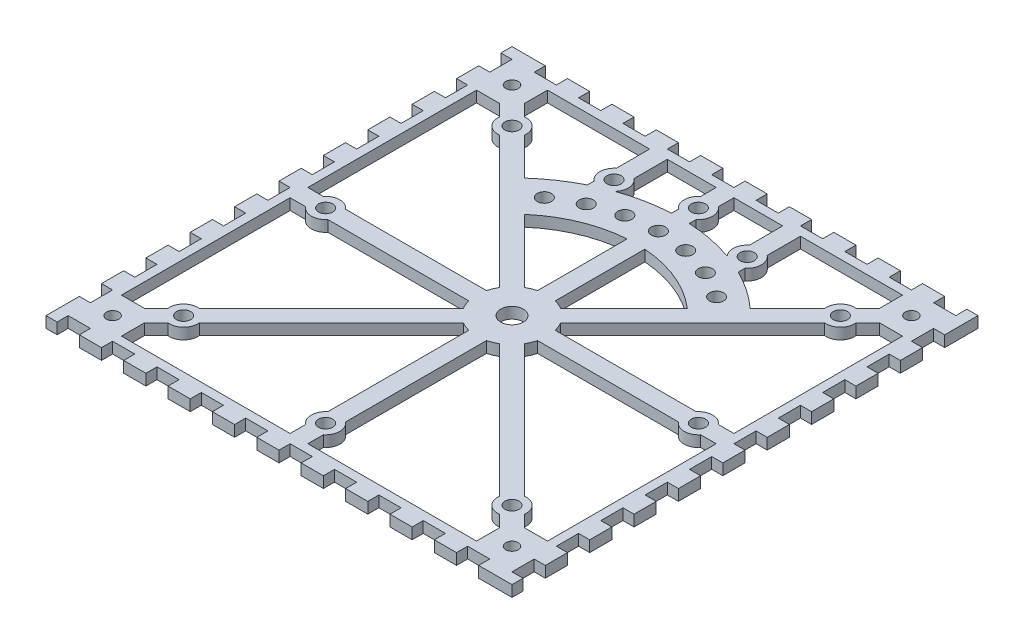
SolidWorks part; units mm, degrees
ref_plane "Front Plane" through (0, 0, 0) normal (0, 0, 1) x (1, 0, 0)
ref_plane "Top Plane" through (0, 0, 0) normal (0, 1, 0) x (1, 0, 0)
ref_plane "Right Plane" through (0, 0, 0) normal (1, 0, 0) x (0, 0, -1)
sketch "Sketch1" plane through (0, 0, 0) normal (0, 1, 0) x (1, 0, 0)
  line L480 (-40, 48) -> (-17, 48)
  line L481 (-48, 40) -> (-48, 2)
  line L483 (-40, -48) -> (-2, -48)
  line L484 (48, 40) -> (48, 2)
  line L486 (48, 2) -> (44.498, 2)
  line L487 (48, -2) -> (48, -40)
  line L488 (40, -42.8284) -> (37.3521, -40.1806)
  line L489 (48, -2) -> (44.498, -2)
  line L490 (-2, -48) -> (-2, -44.498)
  line L491 (2, -48) -> (40, -48)
  line L494 (-40, -42.8284) -> (-37.3521, -40.1806)
  line L496 (-48, -2) -> (-44.498, -2)
  line L497 (-48, 2) -> (-44.498, 2)
  line L498 (-40, 42.8284) -> (-37.3521, 40.1806)
  line L499 (2, 48) -> (2, 44.498)
  line L500 (-33.8194, 36.6479) -> (-25.4186, 28.247)
  line L501 (-36.6479, 33.8194) -> (-6.8914, 4.063)
  line L502 (-2, 39.502) -> (-2, 37.9473)
  line L503 (2, 39.502) -> (2, 37.9473)
  line L504 (33.8194, 36.6479) -> (25.4186, 28.247)
  line L505 (36.6479, 33.8194) -> (6.8914, 4.063)
  line L506 (39.502, 2) -> (7.746, 2)
  line L507 (39.502, -2) -> (7.746, -2)
  line L508 (33.8194, -36.6479) -> (4.063, -6.8914)
  line L509 (36.6479, -33.8194) -> (6.8914, -4.063)
  line L510 (-2, -39.502) -> (-2, -7.746)
  line L511 (2, -39.502) -> (2, -7.746)
  line L513 (-33.8194, -36.6479) -> (-4.063, -6.8914)
  line L514 (-39.502, 2) -> (-7.746, 2)
  line L515 (-39.502, -2) -> (-7.746, -2)
  line L516 (-48, -2) -> (-48, -40)
  line L517 (-42.8284, 40) -> (-40.1806, 37.3521)
  line L518 (-50, 52.5) -> (-45, 52.5)
  line L519 (-45, 52.5) -> (-45, 50)
  line L520 (2, 48) -> (13, 48)
  line L521 (-2, 48) -> (-2, 44.498)
  line L522 (40, 42.8284) -> (37.3521, 40.1806)
  line L523 (42.8284, 40) -> (40.1806, 37.3521)
  line L524 (-45, 50) -> (-40, 50)
  line L525 (-40, 50) -> (-40, 52.5)
  line L526 (-40, 52.5) -> (-35, 52.5)
  line L527 (42.8284, -40) -> (40.1806, -37.3521)
  line L528 (-35, 52.5) -> (-35, 50)
  line L529 (-35, 50) -> (-30, 50)
  line L530 (2, -48) -> (2, -44.498)
  line L531 (-42.8284, -40) -> (-40.1806, -37.3521)
  line L532 (-30, 50) -> (-30, 52.5)
  line L546 (-30, 52.5) -> (-25, 52.5)
  line L547 (-25, 52.5) -> (-25, 50)
  line L548 (-25, 50) -> (-20, 50)
  line L549 (-20, 50) -> (-20, 52.5)
  line L550 (-20, 52.5) -> (-15, 52.5)
  line L551 (-15, 52.5) -> (-15, 50)
  line L552 (-15, 50) -> (-10, 50)
  line L553 (-10, 50) -> (-10, 52.5)
  line L554 (-10, 52.5) -> (-5, 52.5)
  line L555 (-5, 52.5) -> (-5, 50)
  line L556 (-5, 50) -> (0, 50)
  line L557 (0, 50) -> (0, 52.5)
  line L558 (0, 52.5) -> (5, 52.5)
  line L559 (5, 52.5) -> (5, 50)
  line L560 (5, 50) -> (10, 50)
  line L561 (10, 50) -> (10, 52.5)
  line L562 (10, 52.5) -> (15, 52.5)
  line L563 (15, 52.5) -> (15, 50)
  line L564 (15, 50) -> (20, 50)
  line L565 (20, 50) -> (20, 52.5)
  line L566 (20, 52.5) -> (25, 52.5)
  line L567 (25, 52.5) -> (25, 50)
  line L568 (25, 50) -> (30, 50)
  line L569 (30, 50) -> (30, 52.5)
  line L570 (30, 52.5) -> (35, 52.5)
  line L571 (35, 52.5) -> (35, 50)
  line L572 (35, 50) -> (40, 50)
  line L573 (40, 50) -> (40, 52.5)
  line L574 (40, 52.5) -> (45, 52.5)
  line L575 (45, 52.5) -> (45, 50)
  line L576 (45, 50) -> (50, 50)
  line L578 (52.5, 50) -> (52.5, 45)
  line L579 (52.5, 45) -> (50, 45)
  line L580 (50, 45) -> (50, 40)
  line L582 (50, 40) -> (52.5, 40)
  line L583 (52.5, 40) -> (52.5, 35)
  line L584 (52.5, 35) -> (50, 35)
  line L585 (50, 35) -> (50, 30)
  line L586 (50, 30) -> (52.5, 30)
  line L587 (52.5, 30) -> (52.5, 25)
  line L588 (52.5, 25) -> (50, 25)
  line L589 (50, 25) -> (50, 20)
  line L590 (50, 20) -> (52.5, 20)
  line L591 (52.5, 20) -> (52.5, 15)
  line L592 (52.5, 15) -> (50, 15)
  line L593 (50, 15) -> (50, 10)
  line L594 (50, 10) -> (52.5, 10)
  line L595 (52.5, 10) -> (52.5, 5)
  line L596 (52.5, 5) -> (50, 5)
  line L597 (50, 5) -> (50, 0)
  line L598 (50, 0) -> (52.5, 0)
  line L599 (52.5, 0) -> (52.5, -5)
  line L600 (52.5, -5) -> (50, -5)
  line L601 (50, -5) -> (50, -10)
  line L602 (50, -10) -> (52.5, -10)
  line L603 (52.5, -10) -> (52.5, -15)
  line L604 (52.5, -15) -> (50, -15)
  line L605 (50, -15) -> (50, -20)
  line L606 (50, -20) -> (52.5, -20)
  line L607 (52.5, -20) -> (52.5, -25)
  line L608 (52.5, -25) -> (50, -25)
  line L609 (50, -25) -> (50, -30)
  line L610 (50, -30) -> (52.5, -30)
  line L611 (52.5, -30) -> (52.5, -35)
  line L612 (52.5, -35) -> (50, -35)
  line L613 (50, -35) -> (50, -40)
  line L614 (50, -40) -> (52.5, -40)
  line L615 (52.5, -40) -> (52.5, -45)
  line L616 (52.5, -45) -> (50, -45)
  line L617 (50, -45) -> (50, -50)
  line L619 (50, -52.5) -> (45, -52.5)
  line L620 (45, -52.5) -> (45, -50)
  line L621 (45, -50) -> (40, -50)
  line L623 (40, -50) -> (40, -52.5)
  line L624 (40, -52.5) -> (35, -52.5)
  line L625 (35, -52.5) -> (35, -50)
  line L626 (35, -50) -> (30, -50)
  line L627 (30, -50) -> (30, -52.5)
  line L628 (30, -52.5) -> (25, -52.5)
  line L629 (25, -52.5) -> (25, -50)
  line L630 (25, -50) -> (20, -50)
  line L631 (20, -50) -> (20, -52.5)
  line L632 (20, -52.5) -> (15, -52.5)
  line L633 (15, -52.5) -> (15, -50)
  line L634 (15, -50) -> (10, -50)
  line L635 (10, -50) -> (10, -52.5)
  line L636 (10, -52.5) -> (5, -52.5)
  line L637 (5, -52.5) -> (5, -50)
  line L638 (5, -50) -> (0, -50)
  line L639 (0, -50) -> (0, -52.5)
  line L640 (0, -52.5) -> (-5, -52.5)
  line L641 (-5, -52.5) -> (-5, -50)
  line L642 (-5, -50) -> (-10, -50)
  line L643 (-10, -50) -> (-10, -52.5)
  line L644 (-10, -52.5) -> (-15, -52.5)
  line L645 (-15, -52.5) -> (-15, -50)
  line L646 (-15, -50) -> (-20, -50)
  line L647 (-20, -50) -> (-20, -52.5)
  line L648 (-20, -52.5) -> (-25, -52.5)
  line L649 (-25, -52.5) -> (-25, -50)
  line L650 (-25, -50) -> (-30, -50)
  line L651 (-30, -50) -> (-30, -52.5)
  line L652 (-30, -52.5) -> (-35, -52.5)
  line L653 (-35, -52.5) -> (-35, -50)
  line L654 (-35, -50) -> (-40, -50)
  line L655 (-40, -50) -> (-40, -52.5)
  line L656 (-40, -52.5) -> (-45, -52.5)
  line L657 (-45, -52.5) -> (-45, -50)
  line L658 (-45, -50) -> (-50, -50)
  line L660 (-52.5, -50) -> (-52.5, -45)
  line L661 (-52.5, -45) -> (-50, -45)
  line L662 (-50, -45) -> (-50, -40)
  line L664 (-50, -40) -> (-52.5, -40)
  line L665 (-52.5, -40) -> (-52.5, -35)
  line L666 (-52.5, -35) -> (-50, -35)
  line L667 (-50, -35) -> (-50, -30)
  line L668 (-50, -30) -> (-52.5, -30)
  line L669 (-52.5, -30) -> (-52.5, -25)
  line L670 (-52.5, -25) -> (-50, -25)
  line L671 (-50, -25) -> (-50, -20)
  line L672 (-50, -20) -> (-52.5, -20)
  line L673 (-52.5, -20) -> (-52.5, -15)
  line L674 (-52.5, -15) -> (-50, -15)
  line L675 (-50, -15) -> (-50, -10)
  line L676 (-50, -10) -> (-52.5, -10)
  line L677 (-52.5, -10) -> (-52.5, -5)
  line L678 (-52.5, -5) -> (-50, -5)
  line L679 (-50, -5) -> (-50, 0)
  line L680 (-50, 0) -> (-52.5, 0)
  line L681 (-52.5, 0) -> (-52.5, 5)
  line L682 (-52.5, 5) -> (-50, 5)
  line L683 (-50, 5) -> (-50, 10)
  line L684 (-50, 10) -> (-52.5, 10)
  line L685 (-52.5, 10) -> (-52.5, 15)
  line L686 (-52.5, 15) -> (-50, 15)
  line L687 (-50, 15) -> (-50, 20)
  line L688 (-50, 20) -> (-52.5, 20)
  line L689 (-52.5, 20) -> (-52.5, 25)
  line L690 (-52.5, 25) -> (-50, 25)
  line L691 (-50, 25) -> (-50, 30)
  line L692 (-50, 30) -> (-52.5, 30)
  line L693 (-52.5, 30) -> (-52.5, 35)
  line L694 (-52.5, 35) -> (-50, 35)
  line L695 (-50, 35) -> (-50, 40)
  line L696 (-50, 40) -> (-52.5, 40)
  line L697 (-52.5, 40) -> (-52.5, 45)
  line L698 (-52.5, 45) -> (-50, 45)
  line L699 (-50, 45) -> (-50, 50)
  line L703 (-48, 40) -> (-42.8284, 40)
  line L704 (-40, 48) -> (-40, 42.8284)
  line L708 (48, 40) -> (42.8284, 40)
  line L709 (40, 48) -> (40, 42.8284)
  line L713 (48, -40) -> (42.8284, -40)
  line L714 (40, -48) -> (40, -42.8284)
  line L718 (-48, -40) -> (-42.8284, -40)
  line L719 (-40, -48) -> (-40, -42.8284)
  line L720 (-6.8914, -4.063) -> (-36.6479, -33.8194)
  line L725 (-18.3342, 21.1626) -> (-4.063, 6.8914)
  line L726 (18.3342, 21.1626) -> (4.063, 6.8914)
  line L727 (-17, 48) -> (-17, 40.498)
  line L729 (-13, 48) -> (-13, 40.498)
  line L731 (13, 48) -> (13, 40.498)
  line L733 (17, 48) -> (17, 40.498)
  line L735 (-13, 48) -> (-2, 48)
  line L736 (17, 48) -> (40, 48)
  line L737 (-2, 27.9285) -> (-2, 7.746)
  line L738 (2, 27.9285) -> (2, 7.746)
  line L739 (-17, 35.502) -> (-17, 33.9853)
  line L740 (17, 35.502) -> (17, 33.9853)
  line L743 (-50, 50) -> (-52.5, 50)
  line L745 (-50, 52.5) -> (-52.5, 52.5)
  line L746 (-52.5, 50) -> (-52.5, 52.5)
  line L749 (52.5, 50) -> (52.5, 52.5)
  line L750 (52.5, 52.5) -> (50, 52.5)
  line L751 (50, 50) -> (50, 52.5)
  line L753 (50, -50) -> (52.5, -50)
  line L755 (50, -52.5) -> (52.5, -52.5)
  line L756 (52.5, -50) -> (52.5, -52.5)
  line L759 (-52.5, -50) -> (-52.5, -52.5)
  line L760 (-52.5, -52.5) -> (-50, -52.5)
  line L761 (-50, -50) -> (-50, -52.5)
  circle A10 centre (0, 0) radius 2.55
  arc A14 (-6.8914, 4.063) -> (-7.746, 2) centre (0, 0) ccw
  arc A15 (4.063, 6.8914) -> (2, 7.746) centre (0, 0) ccw
  arc A16 (6.8914, -4.063) -> (7.746, -2) centre (0, 0) ccw
  arc A17 (-4.063, -6.8914) -> (-2, -7.746) centre (0, 0) ccw
  circle A51 centre (37, -37) radius 1.6
  circle A52 centre (-37, -37) radius 1.6
  circle A53 centre (-37, 37) radius 1.6
  circle A56 centre (37, 37) radius 1.6
  arc A73 (-7.746, -2) -> (-6.8914, -4.063) centre (0, 0) ccw
  arc A74 (-2, 7.746) -> (-4.063, 6.8914) centre (0, 0) ccw
  arc A75 (2, -7.746) -> (4.063, -6.8914) centre (0, 0) ccw
  arc A76 (7.746, 2) -> (6.8914, 4.063) centre (0, 0) ccw
  arc A85 (-40.1806, 37.3521) -> (-36.6479, 33.8194) centre (-37, 37) ccw
  arc A86 (36.6479, 33.8194) -> (40.1806, 37.3521) centre (37, 37) ccw
  arc A87 (33.8194, -36.6479) -> (37.3521, -40.1806) centre (37, -37) ccw
  circle A88 centre (0, 42) radius 1.6
  circle A89 centre (42, 0) radius 1.6
  circle A90 centre (-42, 0) radius 1.6
  circle A91 centre (0, -42) radius 1.6
  arc A92 (-44.498, -2) -> (-39.502, -2) centre (-42, 0) ccw
  arc A93 (-2, 44.498) -> (-2, 39.502) centre (0, 42) ccw
  arc A94 (39.502, -2) -> (44.498, -2) centre (42, 0) ccw
  arc A95 (-2, -39.502) -> (-2, -44.498) centre (0, -42) ccw
  arc A96 (-39.502, 2) -> (-44.498, 2) centre (-42, 0) ccw
  arc A97 (2, 39.502) -> (2, 44.498) centre (0, 42) ccw
  arc A98 (44.498, 2) -> (39.502, 2) centre (42, 0) ccw
  arc A99 (2, -44.498) -> (2, -39.502) centre (0, -42) ccw
  arc A100 (-37.3521, -40.1806) -> (-33.8194, -36.6479) centre (-37, -37) ccw
  arc A101 (-33.8194, 36.6479) -> (-37.3521, 40.1806) centre (-37, 37) ccw
  arc A102 (37.3521, 40.1806) -> (33.8194, 36.6479) centre (37, 37) ccw
  arc A103 (40.1806, -37.3521) -> (36.6479, -33.8194) centre (37, -37) ccw
  arc A104 (-36.6479, -33.8194) -> (-40.1806, -37.3521) centre (-37, -37) ccw
  circle A131 centre (-45, 45) radius 1.4
  circle A132 centre (45, 45) radius 1.4
  circle A133 centre (-45, -45) radius 1.4
  circle A134 centre (45, -45) radius 1.4
  circle A135 centre (0, 0) radius 33 construction
  arc A137 (18.3342, 21.1626) -> (2, 27.9285) centre (0, 0) ccw construction
  circle A138 centre (-15, 38) radius 1.6
  circle A139 centre (15, 38) radius 1.6
  arc A140 (18.3342, 21.1626) -> (2, 27.9285) centre (0, 0) ccw
  arc A142 (12.6437, 35.8349) -> (2, 37.9473) centre (0, 0) ccw construction
  arc A143 (12.6437, 35.8349) -> (2, 37.9473) centre (0, 0) ccw
  arc A144 (25.4186, 28.247) -> (17, 33.9853) centre (0, 0) ccw construction
  arc A145 (25.4186, 28.247) -> (17, 33.9853) centre (0, 0) ccw
  arc A146 (-17, 33.9853) -> (-25.4186, 28.247) centre (0, 0) ccw construction
  arc A147 (-17, 33.9853) -> (-25.4186, 28.247) centre (0, 0) ccw
  arc A148 (-2, 37.9473) -> (-12.6437, 35.8349) centre (0, 0) ccw construction
  arc A149 (-2, 37.9473) -> (-12.6437, 35.8349) centre (0, 0) ccw
  arc A150 (-2, 27.9285) -> (-18.3342, 21.1626) centre (0, 0) ccw construction
  arc A151 (-2, 27.9285) -> (-18.3342, 21.1626) centre (0, 0) ccw
  arc A152 (-17, 40.498) -> (-17, 35.502) centre (-15, 38) ccw
  arc A153 (13, 40.498) -> (12.6437, 35.8349) centre (15, 38) ccw
  arc A154 (-12.6437, 35.8349) -> (-13, 40.498) centre (-15, 38) ccw
  arc A155 (17, 35.502) -> (17, 40.498) centre (15, 38) ccw
  circle A156 centre (0, 33) radius 1.6
  circle A157 centre (6.8611, 32.2789) radius 1.6
  circle A158 centre (13.4223, 30.147) radius 1.6
  circle A159 centre (19.3969, 26.6976) radius 1.6
  circle A183 centre (-19.3969, 26.6976) radius 1.6
  circle A184 centre (-13.4223, 30.147) radius 1.6
  circle A185 centre (-6.8611, 32.2789) radius 1.6
  circle A186 centre (0, 0) radius 28 construction
  circle A187 centre (0, 0) radius 38 construction
  dimension "D6" = 4
  dimension "D7" = 4
  dimension "D4" = 10
  dimension "D1" = 10
  dimension "D3" = 10
  dimension "D2" = 10
extrude "Boss-Extrude1" add sketch "Sketch1" along normal blind 2.5
